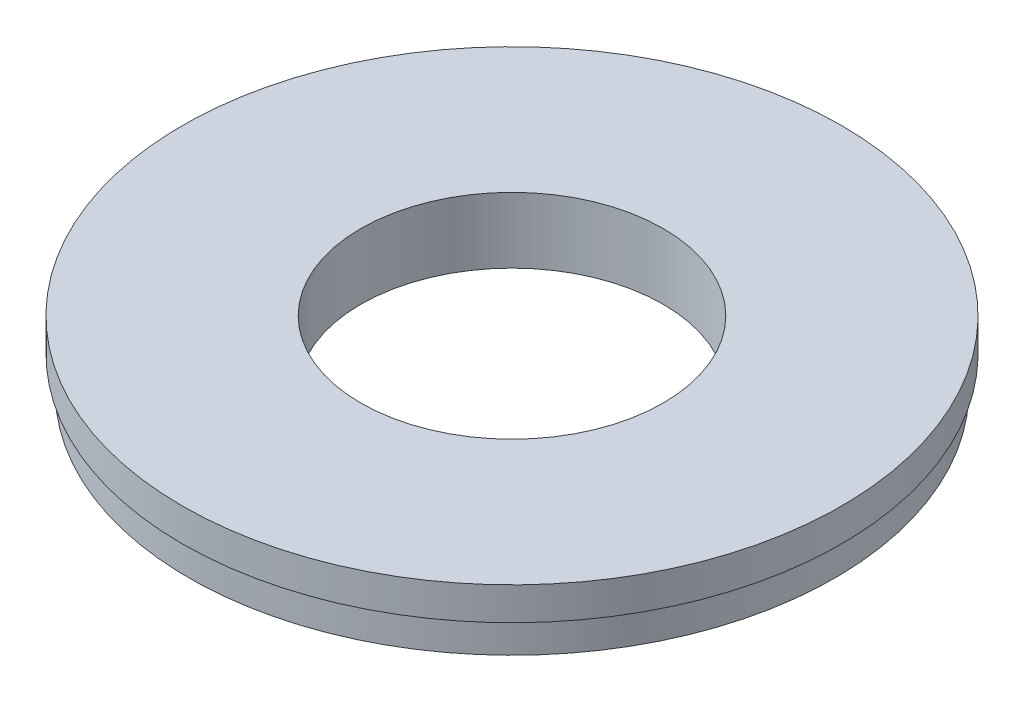
SolidWorks part; units mm, degrees
ref_plane "Front Plane" through (0, 0, 0) normal (0, 0, 1) x (1, 0, 0)
ref_plane "Top Plane" through (0, 0, 0) normal (0, 1, 0) x (1, 0, 0)
ref_plane "Right Plane" through (0, 0, 0) normal (1, 0, 0) x (0, 0, -1)
sketch "Sketch1" plane through (0, 0, 0) normal (0, 0, 1) x (1, 0, 0)
  line L0 (0, 0) -> (0, 11.938) construction
  line L1 (27.5, 11.938) -> (59.944, 11.938)
  line L2 (59.944, 11.938) -> (59.944, 5.969)
  line L3 (27.5, 0) -> (58.7502, 0)
  line L4 (59.944, 5.969) -> (58.7502, 5.969)
  line L5 (58.7502, 5.969) -> (58.7502, 0)
  line L6 (27.5, 11.938) -> (27.5, 0)
  line L7 (0, 11.938) -> (27.5, 11.938) construction
  line L8 (0, 0) -> (27.5, 0) construction
  dimension "D1" = 59.944
  dimension "D2" = 11.938
  dimension "D3" = 1.1938
  dimension "D4" = 5.969
  dimension "D5" = 27.5
revolve "Revolve1" add sketch "Sketch1" angle 360 about L0
